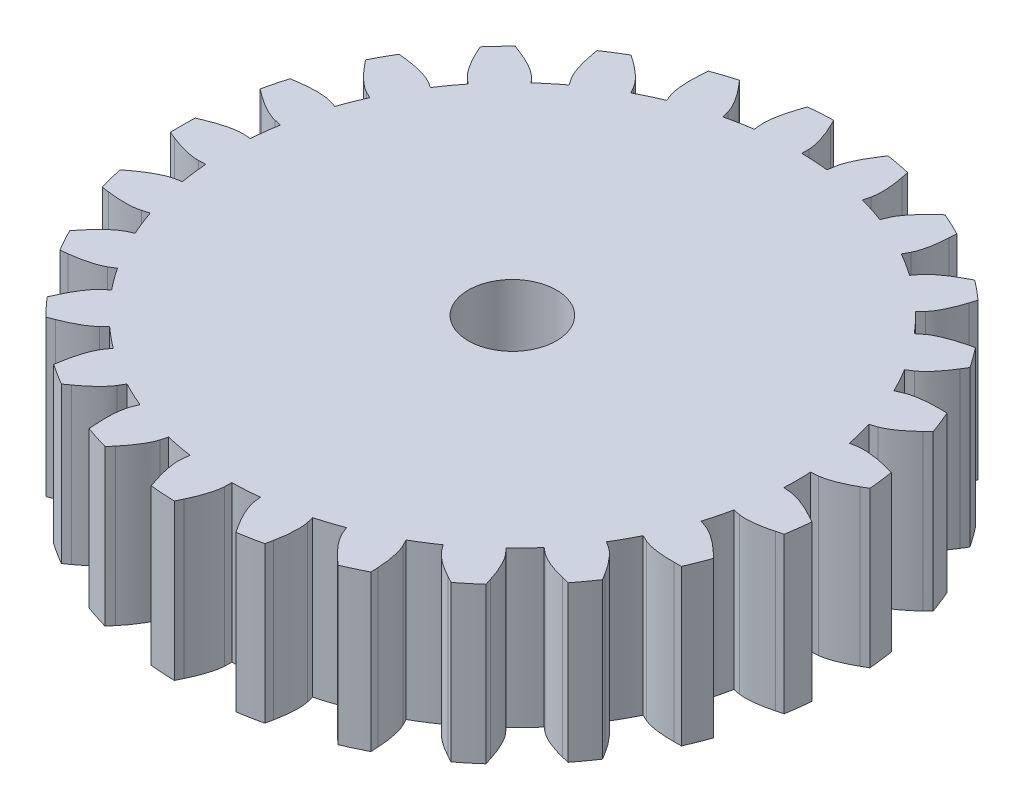
SolidWorks part; units mm, degrees
ref_plane "Front Plane" through (0, 0, 0) normal (0, 0, 1) x (1, 0, 0)
ref_plane "Top Plane" through (0, 0, 0) normal (0, 1, 0) x (1, 0, 0)
ref_plane "Right Plane" through (0, 0, 0) normal (1, 0, 0) x (0, 0, -1)
sketch "Sketch1" plane through (0, 0, 0) normal (0, 1, 0) x (1, 0, 0)
  line L0 (0, 30) -> (-129.8026, 30) construction
  line L1 (-99.777, -6.3159) -> (118.111, 72.9889) construction
  circle A0 centre (0, 0) radius 30
  circle A1 centre (0, 0) radius 28.1908
  dimension "D1" = 60
  dimension "D2" = 20
sketch "Sketch2" plane through (0, 0, 0) normal (0, 1, 0) x (1, 0, 0)
  line L0 (0, 0) -> (-9.6418, 26.4907) construction
  line L1 (-99.777, -6.3159) -> (118.111, 72.9889) construction
  line L2 (-9.6418, 26.4907) -> (0, 30)
  line L3 (-10.3543, 26.2204) -> (0, 0) construction
  line L4 (-10.3543, 26.2204) -> (-0.1021, 30.2689) construction
  line L5 (0, 0) -> (-11.0591, 25.931) construction
  line L6 (0, 0) -> (-11.7559, 25.6226) construction
  line L7 (-12.4441, 25.2955) -> (0, 0) construction
  line L8 (0, 0) -> (-13.1232, 24.95) construction
  line L9 (-8.9223, 26.7416) -> (0.088, 29.7479) construction
  line L10 (-11.0591, 25.931) -> (-0.2192, 30.554) construction
  line L11 (-11.7559, 25.6226) -> (-0.3523, 30.8547) construction
  line L12 (-12.4441, 25.2955) -> (-0.5023, 31.1703) construction
  line L13 (-6.7269, 27.3764) -> (0.2773, 29.0975) construction
  line L14 (-7.4643, 27.1846) -> (0.2256, 29.2961) construction
  line L15 (-5.9846, 27.5482) -> (0.319, 28.9176) construction
  line L16 (-8.1963, 26.973) -> (0.1629, 29.5131) construction
  line L17 (-5.2378, 27.6999) -> (0.3517, 28.7569) construction
  circle A0 centre (0, 0) radius 28.1908 construction
  arc A1 (-9.6418, 26.4907) -> (-10.3543, 26.2204) centre (0, 0) ccw
  arc A2 (-10.3543, 26.2204) -> (-11.0591, 25.931) centre (0, 0) ccw
  arc A3 (-11.0591, 25.931) -> (-11.7559, 25.6226) centre (0, 0) ccw
  arc A4 (-11.7559, 25.6226) -> (-12.4441, 25.2955) centre (0, 0) ccw
  arc A5 (-12.4441, 25.2955) -> (-13.1232, 24.95) centre (0, 0) ccw
  arc A6 (-9.6418, 26.4907) -> (-8.9223, 26.7416) centre (0, 0) cw
  arc A7 (-8.9223, 26.7416) -> (-8.1963, 26.973) centre (0, 0) cw
  arc A8 (-8.1963, 26.973) -> (-7.4643, 27.1846) centre (0, 0) cw
  arc A9 (-7.4643, 27.1846) -> (-6.7269, 27.3764) centre (0, 0) cw
  arc A10 (-6.7269, 27.3764) -> (-5.9846, 27.5482) centre (0, 0) cw
  arc A11 (-5.9846, 27.5482) -> (-5.2378, 27.6999) centre (0, 0) cw
  dimension "D1" = 10.2606
  dimension "D3" = 11.0226
  dimension "D8" = 11.7846
  dimension "D9" = 12.5466
  dimension "D10" = 13.3086
  dimension "D15" = 9.4986
  dimension "D16" = 8.7366
  dimension "D17" = 7.9746
  dimension "D18" = 7.2126
  dimension "D21" = 6.4506
  dimension "D22" = 5.6886
  dimension "D2" = 0.762
  dimension "D4" = 0.762
  dimension "D5" = 0.762
  dimension "D6" = 0.762
  dimension "D7" = 0.762
  dimension "D11" = 0.762
  dimension "D12" = 0.762
  dimension "D13" = 0.762
  dimension "D14" = 0.762
  dimension "D19" = 0.762
  dimension "D20" = 0.762
sketch "Sketch4" plane through (0, 0, 0) normal (0, 1, 0) x (1, 0, 0)
  line L0 (0, 0) -> (0, 39.7853) construction
  line L1 (0, 0) -> (-2.5084, 39.8703) construction
  circle A0 centre (0, 0) radius 28.1908 construction
  circle A1 centre (0, 0) radius 31.81
  circle A2 centre (0, 0) radius 30 construction
  spline S0 degree 3 poles (-0.5023, 31.1703) (-0.4025, 30.9674) (-0.2649, 30.6686) (-0.1033, 30.2758) (-0.0012, 30.0069) (0.0869, 29.7547) (0.1619, 29.52) (0.2247, 29.303) (0.2766, 29.1044) (0.3615, 28.7384) (0.4102, 28.4344) (0.4191, 28.1877) knots 0 0 0 0 0.215965 0.31411 0.405697 0.490726 0.569196 0.641109 0.706463 0.765259 1 1 1 1
  spline S1 degree 3 poles (-3.4083, 30.9875) (-3.4819, 30.7737) (-3.581, 30.46) (-3.692, 30.05) (-3.7597, 29.7704) (-3.8155, 29.5092) (-3.8604, 29.2669) (-3.8956, 29.0438) (-3.9221, 28.8402) (-3.9605, 28.4664) (-3.9707, 28.1588) (-3.9486, 27.9129) knots 0 0 0 0 0.215965 0.31411 0.405697 0.490726 0.569196 0.641109 0.706463 0.765259 1 1 1 1
  spline S2 degree 2 poles (-3.4083, 30.9875) (-3.2603, 31.434) (-3.1869, 31.65) knots 0 0 0 1 1 1
  spline S3 degree 2 poles (-0.5023, 31.1703) (-0.7051, 31.5947) (-0.805, 31.7998) knots 0 0 0 1 1 1
  dimension "D2" = 1.81
  dimension "D1" = 3.6
sketch "Sketch5" plane through (0, 0, 0) normal (0, 1, 0) x (1, 0, 0)
  circle A1 centre (0, 0) radius 27.5
  dimension "D1" = 55
extrude "Boss-Extrude1" add sketch "Sketch5" along normal blind 15
sketch "Sketch7" plane through (0, 0, 0) normal (0, 1, 0) x (1, 0, 0)
  line L0 (0.4191, 28.1877) -> (0.4191, 27.4968)
  circle A2 centre (0, 0) radius 27.5
  arc A3 (0.4191, 27.4968) -> (-3.8796, 27.225) centre (0, 0) ccw
  circle A5 centre (0, 0) radius 31.81
  arc A6 (-0.805, 31.7998) -> (-3.1869, 31.65) centre (0, 0) ccw
  spline S2 degree 2 poles (1274.8199, -2684.1688) (-1275.8104, 2748.1183) (1273.1943, -2684.1016) knots -109.339646 -109.339646 -109.339646 113.20807 113.20807 113.20807 only from (-0.5023, 31.1703) to (-0.805, 31.7998)
  spline S3 degree 2 poles (-0.5023, 31.1703) (-0.7051, 31.5947) (-0.805, 31.7998) knots 0 0 0 1 1 1
  spline S5 degree 3 poles (2998.75, -30.18) (-181.7072, 31.7269) (-13.9419, 63.9356) (-0.1033, 30.2758) (-0.0012, 30.0069) (0.0869, 29.7547) (0.1619, 29.52) (0.2247, 29.303) (0.2766, 29.1044) (3.4004, 15.6431) (-35.1593, -6.9752) (-2993.4136, -158.0668) knots -34.354648 -34.354648 -34.354648 -34.354648 0.215965 0.31411 0.405697 0.490726 0.569196 0.641109 0.706463 0.765259 13.840232 13.840232 13.840232 13.840232 only from (-0.5023, 31.1703) to (0.4191, 28.1877)
  spline S6 degree 3 poles (-0.5023, 31.1703) (-0.4025, 30.9674) (-0.2649, 30.6686) (-0.1033, 30.2758) (-0.0012, 30.0069) (0.0869, 29.7547) (0.1619, 29.52) (0.2247, 29.303) (0.2766, 29.1044) (0.3615, 28.7384) (0.4102, 28.4344) (0.4191, 28.1877) knots 0 0 0 0 0.215965 0.31411 0.405697 0.490726 0.569196 0.641109 0.706463 0.765259 1 1 1 1
  spline S8 degree 2 poles (-928.352, -2822.7807) (921.3197, 2886.35) (-926.7476, -2822.5102) knots -109.339646 -109.339646 -109.339646 113.20807 113.20807 113.20807 only from (-3.4083, 30.9875) to (-3.1869, 31.65)
  spline S9 degree 2 poles (-3.4083, 30.9875) (-3.2603, 31.434) (-3.1869, 31.65) knots 0 0 0 1 1 1
  spline S10 degree 1 poles (-3.9486, 27.9129) (-3.8796, 27.225) knots 0 0 1 1
  spline S11 degree 3 poles (-2971.3214, -405.785) (176.2979, 54.2507) (5.8187, 65.1788) (-3.692, 30.05) (-3.7597, 29.7704) (-3.8155, 29.5092) (-3.8604, 29.2669) (-3.8956, 29.0438) (-3.9221, 28.8402) (-5.3342, 15.0936) (35.7563, -2.5136) (2989.6206, 218.3538) knots -34.354648 -34.354648 -34.354648 -34.354648 0.215965 0.31411 0.405697 0.490726 0.569196 0.641109 0.706463 0.765259 13.840232 13.840232 13.840232 13.840232 only from (-3.4083, 30.9875) to (-3.9486, 27.9129)
  spline S12 degree 3 poles (-3.4083, 30.9875) (-3.4819, 30.7737) (-3.581, 30.46) (-3.692, 30.05) (-3.7597, 29.7704) (-3.8155, 29.5092) (-3.8604, 29.2669) (-3.8956, 29.0438) (-3.9221, 28.8402) (-3.9605, 28.4664) (-3.9707, 28.1588) (-3.9486, 27.9129) knots 0 0 0 0 0.215965 0.31411 0.405697 0.490726 0.569196 0.641109 0.706463 0.765259 1 1 1 1
  dimension "D1" = 0
  dimension "D2" = 0
  dimension "D3" = 0
  dimension "D4" = 0
  dimension "D5" = 0
  dimension "D6" = 0
extrude "Boss-Extrude2" add sketch "Sketch7" along normal blind 15
sketch "Sketch8" plane through (0, 0, 0) normal (1, 0, 0) x (0, 0, -1)
  line L0 (0, 0) -> (-0.0016, 15) construction
  line L1 (27.4968, 15) -> (-27.5, 15) construction
pattern_circular "CirPattern2" count 25 over 360 about axis through (0, 15, 0) along (0, 1, 0) of "Boss-Extrude2"
sketch "Sketch9" plane through (0, 15, 0) normal (0, 1, 0) x (1, 0, 0)
  circle A0 centre (0, 0) radius 4.25
  dimension "D1" = 8.5
extrude "Cut-Extrude1" cut sketch "Sketch9" against normal through all
equation "\"D3@Sketch2\"=\"D1@Sketch2\"+\"D2@Sketch2\""
equation "\"D4@Sketch2\"=\"D2@Sketch2\""
equation "\"D5@Sketch2\"=\"D2@Sketch2\""
equation "\"D6@Sketch2\"=\"D2@Sketch2\""
equation "\"D7@Sketch2\"=\"D2@Sketch2\""
equation "\"D8@Sketch2\"=\"D3@Sketch2\"+\"D2@Sketch2\""
equation "\"D9@Sketch2\"=\"D8@Sketch2\"+\"D2@Sketch2\""
equation "\"D12@Sketch2\"=\"D11@Sketch2\""
equation "\"D13@Sketch2\"=\"D12@Sketch2\""
equation "\"D14@Sketch2\"=\"D12@Sketch2\""
equation "\"D15@Sketch2\"=\"D1@Sketch2\"-\"D11@Sketch2\""
equation "\"D16@Sketch2\"=\"D15@Sketch2\"-\"D11@Sketch2\""
equation "\"D17@Sketch2\"=\"D16@Sketch2\"-\"D11@Sketch2\""
equation "\"D18@Sketch2\"=\"D17@Sketch2\"-\"D11@Sketch2\""
equation "\"D10@Sketch2\"=\"D1@Sketch2\" + 4*\"D11@Sketch2\""
equation "\"D21@Sketch2\"=\"D18@Sketch2\"-\"D11@Sketch2\""
equation "\"D22@Sketch2\"=\"D21@Sketch2\"-\"D11@Sketch2\""
